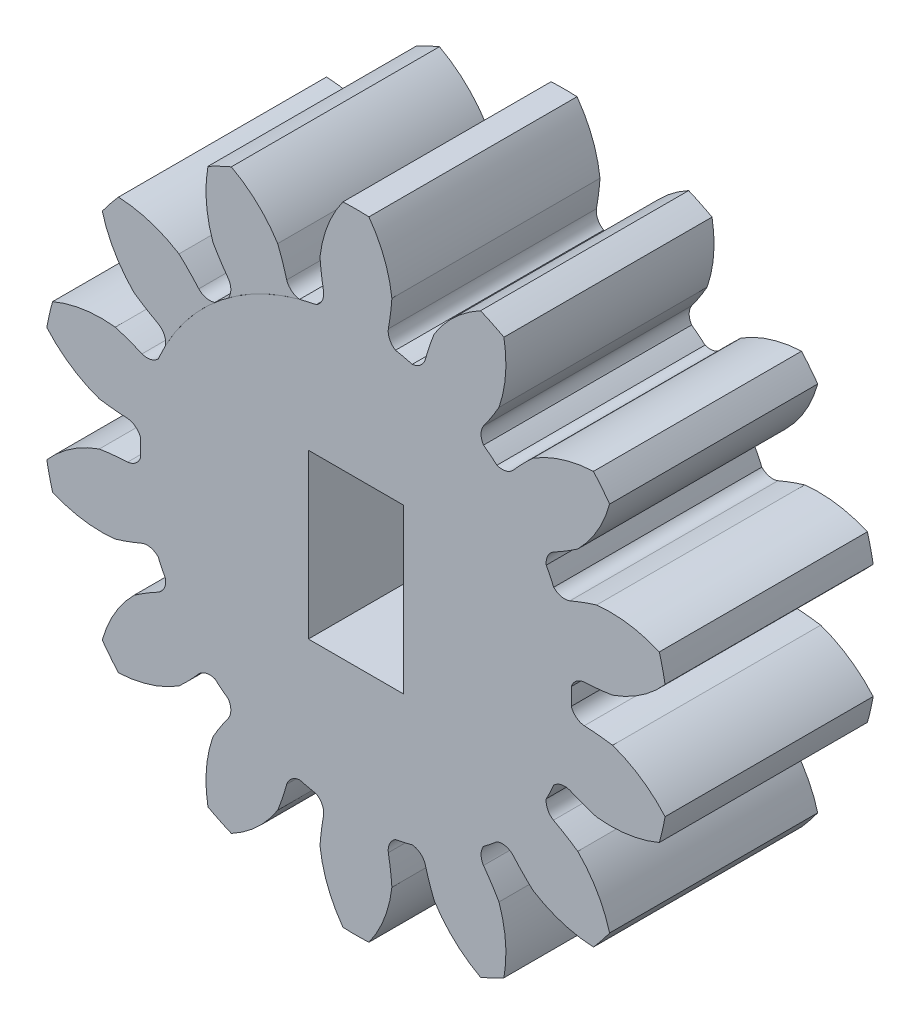
SolidWorks part; units mm, degrees
ref_plane "Front Plane" through (0, 0, 0) normal (0, 0, 1) x (1, 0, 0)
ref_plane "Top Plane" through (0, 0, 0) normal (0, 1, 0) x (1, 0, 0)
ref_plane "Right Plane" through (0, 0, 0) normal (1, 0, 0) x (0, 0, -1)
ref_plane "Plane1" through (0, 0, 20) normal (0, 0, 1) x (1, 0, 0)
ref_plane "Plane2" through (0, 0, 27) normal (0, 0, 1) x (1, 0, 0)
sketch "Sketch1" plane through (0, 0, 20) normal (0, 0, 1) x (1, 0, 0)
  circle A1 centre (0, 20.9252) radius 7.25
  dimension "D1" = 14.5
sketch "Sketch2" plane through (0, 0, 20) normal (0, 0, 1) x (1, 0, 0)
  arc A0 (-0.4364, 31.4909) -> (0.4364, 31.4909) centre (0, 22.3663) cw
  arc A1 (0.4364, 31.4909) -> (1.2091, 29.5028) centre (-2.9453, 29.0324) cw
  arc A2 (1.2091, 29.5028) -> (1.0888, 28.5542) centre (-7.3823, 30.1104) cw
  arc A3 (1.0888, 28.5542) -> (1.3305, 28.0521) centre (1.5953, 28.4888) ccw
  circle A4 centre (0, 20.9252) radius 7.25 construction
  arc A5 (-1.0888, 28.5542) -> (-1.3305, 28.0521) centre (-1.5953, 28.4888) cw
  arc A6 (-1.2091, 29.5028) -> (-1.0888, 28.5542) centre (7.3823, 30.1104) ccw
  arc A7 (-0.4364, 31.4909) -> (-1.2091, 29.5028) centre (2.9453, 29.0324) ccw
  arc A8 (-1.3305, 28.0521) -> (1.3305, 28.0521) centre (0, 20.9252) cw
  arc A9 (1.8935, 27.9236) -> (4.291, 26.769) centre (0, 20.9252) cw
  arc A10 (4.291, 27.3263) -> (4.291, 26.769) centre (4.719, 27.0476) ccw
  arc A11 (4.811, 28.1288) -> (4.291, 27.3263) centre (-2.6659, 32.4038) cw
  arc A12 (4.9774, 30.2553) -> (4.811, 28.1288) centre (0.8639, 29.5075) cw
  arc A13 (4.1911, 30.6339) -> (4.9774, 30.2553) centre (0.6252, 22.2236) cw
  arc A14 (4.1911, 30.6339) -> (2.6323, 29.178) centre (6.1712, 26.9516) ccw
  arc A15 (2.6323, 29.178) -> (2.3291, 28.2711) centre (10.6365, 25.9977) ccw
  arc A16 (2.3291, 28.2711) -> (1.8935, 27.9236) centre (1.8444, 28.432) cw
  arc A17 (4.7424, 26.409) -> (6.4016, 24.3285) centre (0, 20.9252) cw
  arc A18 (6.6434, 24.8306) -> (6.4016, 24.3285) centre (6.9081, 24.3938) ccw
  arc A19 (7.4601, 25.328) -> (6.6434, 24.8306) centre (2.5785, 32.4238) cw
  arc A20 (8.5327, 27.1717) -> (7.4601, 25.328) centre (4.502, 28.2827) cw
  arc A21 (7.9885, 27.854) -> (8.5327, 27.1717) centre (1.1267, 21.8237) cw
  arc A22 (7.9885, 27.854) -> (5.9524, 27.2186) centre (8.1748, 23.6772) ccw
  arc A23 (5.9524, 27.2186) -> (5.2857, 26.533) centre (11.784, 20.8804) ccw
  arc A24 (5.2857, 26.533) -> (4.7424, 26.409) centre (4.9188, 26.8883) cw
  arc A25 (6.6521, 23.8083) -> (7.2442, 21.2139) centre (0, 20.9252) cw
  arc A26 (7.68, 21.5614) -> (7.2442, 21.2139) centre (7.729, 21.053) ccw
  arc A27 (8.6316, 21.6552) -> (7.68, 21.5614) centre (7.3121, 30.1663) cw
  arc A28 (10.3979, 22.8509) -> (8.6316, 21.6552) centre (7.2485, 25.6007) cw
  arc A29 (10.2037, 23.7018) -> (10.3979, 22.8509) centre (1.4049, 21.2459) cw
  arc A30 (10.2037, 23.7018) -> (8.0935, 24.0127) centre (8.5593, 19.8578) ccw
  arc A31 (8.0935, 24.0127) -> (7.1954, 23.6843) centre (10.5976, 15.7719) ccw
  arc A32 (7.1954, 23.6843) -> (6.6521, 23.8083) centre (7.019, 24.1636) cw
  arc A33 (7.2442, 20.6365) -> (6.6521, 18.0422) centre (0, 20.9252) cw
  arc A34 (7.1954, 18.1662) -> (6.6521, 18.0422) centre (7.019, 17.6869) ccw
  arc A35 (8.0935, 17.8378) -> (7.1954, 18.1662) centre (10.5976, 26.0785) cw
  arc A36 (10.2037, 18.1487) -> (8.0935, 17.8378) centre (8.5593, 21.9927) cw
  arc A37 (10.3979, 18.9996) -> (10.2037, 18.1487) centre (1.4049, 20.6046) cw
  arc A38 (10.3979, 18.9996) -> (8.6316, 20.1953) centre (7.2485, 16.2497) ccw
  arc A39 (8.6316, 20.1953) -> (7.68, 20.2891) centre (7.3121, 11.6842) ccw
  arc A40 (7.68, 20.2891) -> (7.2442, 20.6365) centre (7.729, 20.7975) cw
  arc A41 (6.4016, 17.522) -> (4.7424, 15.4415) centre (0, 20.9252) cw
  arc A42 (5.2857, 15.3174) -> (4.7424, 15.4415) centre (4.9188, 14.9621) ccw
  arc A43 (5.9524, 14.6319) -> (5.2857, 15.3174) centre (11.784, 20.9701) cw
  arc A44 (7.9885, 13.9965) -> (5.9524, 14.6319) centre (8.1748, 18.1733) cw
  arc A45 (8.5327, 14.6788) -> (7.9885, 13.9965) centre (1.1267, 20.0268) cw
  arc A46 (8.5327, 14.6788) -> (7.4601, 16.5225) centre (4.502, 13.5677) ccw
  arc A47 (7.4601, 16.5225) -> (6.6434, 17.0199) centre (2.5785, 9.4267) ccw
  arc A48 (6.6434, 17.0199) -> (6.4016, 17.522) centre (6.9081, 17.4567) cw
  arc A49 (4.291, 15.0815) -> (1.8935, 13.9269) centre (0, 20.9252) cw
  arc A50 (2.3291, 13.5794) -> (1.8935, 13.9269) centre (1.8444, 13.4185) ccw
  arc A51 (2.6323, 12.6725) -> (2.3291, 13.5794) centre (10.6365, 15.8528) cw
  arc A52 (4.1911, 11.2165) -> (2.6323, 12.6725) centre (6.1712, 14.8989) cw
  arc A53 (4.9774, 11.5952) -> (4.1911, 11.2165) centre (0.6252, 19.6269) cw
  arc A54 (4.9774, 11.5952) -> (4.811, 13.7217) centre (0.8639, 12.343) ccw
  arc A55 (4.811, 13.7217) -> (4.291, 14.5242) centre (-2.6659, 9.4467) ccw
  arc A56 (4.291, 14.5242) -> (4.291, 15.0815) centre (4.719, 14.8028) cw
  arc A57 (1.3305, 13.7984) -> (-1.3305, 13.7984) centre (0, 20.9252) cw
  arc A58 (-1.0888, 13.2963) -> (-1.3305, 13.7984) centre (-1.5953, 13.3616) ccw
  arc A59 (-1.2091, 12.3476) -> (-1.0888, 13.2963) centre (7.3823, 11.7401) cw
  arc A60 (-0.4364, 10.3595) -> (-1.2091, 12.3476) centre (2.9453, 12.8181) cw
  arc A61 (0.4364, 10.3595) -> (-0.4364, 10.3595) centre (0, 19.4842) cw
  arc A62 (0.4364, 10.3595) -> (1.2091, 12.3476) centre (-2.9453, 12.8181) ccw
  arc A63 (1.2091, 12.3476) -> (1.0888, 13.2963) centre (-7.3823, 11.7401) ccw
  arc A64 (1.0888, 13.2963) -> (1.3305, 13.7984) centre (1.5953, 13.3616) cw
  arc A65 (-1.8935, 13.9269) -> (-4.291, 15.0815) centre (0, 20.9252) cw
  arc A66 (-4.291, 14.5242) -> (-4.291, 15.0815) centre (-4.719, 14.8028) ccw
  arc A67 (-4.811, 13.7217) -> (-4.291, 14.5242) centre (2.6659, 9.4467) cw
  arc A68 (-4.9774, 11.5952) -> (-4.811, 13.7217) centre (-0.8639, 12.343) cw
  arc A69 (-4.1911, 11.2165) -> (-4.9774, 11.5952) centre (-0.6252, 19.6269) cw
  arc A70 (-4.1911, 11.2165) -> (-2.6323, 12.6725) centre (-6.1712, 14.8989) ccw
  arc A71 (-2.6323, 12.6725) -> (-2.3291, 13.5794) centre (-10.6365, 15.8528) ccw
  arc A72 (-2.3291, 13.5794) -> (-1.8935, 13.9269) centre (-1.8444, 13.4185) cw
  arc A73 (-4.7424, 15.4415) -> (-6.4016, 17.522) centre (0, 20.9252) cw
  arc A74 (-6.6434, 17.0199) -> (-6.4016, 17.522) centre (-6.9081, 17.4567) ccw
  arc A75 (-7.4601, 16.5225) -> (-6.6434, 17.0199) centre (-2.5785, 9.4267) cw
  arc A76 (-8.5327, 14.6788) -> (-7.4601, 16.5225) centre (-4.502, 13.5677) cw
  arc A77 (-7.9885, 13.9965) -> (-8.5327, 14.6788) centre (-1.1267, 20.0268) cw
  arc A78 (-7.9885, 13.9965) -> (-5.9524, 14.6319) centre (-8.1748, 18.1733) ccw
  arc A79 (-5.9524, 14.6319) -> (-5.2857, 15.3174) centre (-11.784, 20.9701) ccw
  arc A80 (-5.2857, 15.3174) -> (-4.7424, 15.4415) centre (-4.9188, 14.9621) cw
  arc A81 (-6.6521, 18.0422) -> (-7.2442, 20.6365) centre (0, 20.9252) cw
  arc A82 (-7.68, 20.2891) -> (-7.2442, 20.6365) centre (-7.729, 20.7975) ccw
  arc A83 (-8.6316, 20.1953) -> (-7.68, 20.2891) centre (-7.3121, 11.6842) cw
  arc A84 (-10.3979, 18.9996) -> (-8.6316, 20.1953) centre (-7.2485, 16.2497) cw
  arc A85 (-10.2037, 18.1487) -> (-10.3979, 18.9996) centre (-1.4049, 20.6046) cw
  arc A86 (-10.2037, 18.1487) -> (-8.0935, 17.8378) centre (-8.5593, 21.9927) ccw
  arc A87 (-8.0935, 17.8378) -> (-7.1954, 18.1662) centre (-10.5976, 26.0785) ccw
  arc A88 (-7.1954, 18.1662) -> (-6.6521, 18.0422) centre (-7.019, 17.6869) cw
  arc A89 (-7.2442, 21.2139) -> (-6.6521, 23.8083) centre (0, 20.9252) cw
  arc A90 (-7.1954, 23.6843) -> (-6.6521, 23.8083) centre (-7.019, 24.1636) ccw
  arc A91 (-8.0935, 24.0127) -> (-7.1954, 23.6843) centre (-10.5976, 15.7719) cw
  arc A92 (-10.2037, 23.7018) -> (-8.0935, 24.0127) centre (-8.5593, 19.8578) cw
  arc A93 (-10.3979, 22.8509) -> (-10.2037, 23.7018) centre (-1.4049, 21.2459) cw
  arc A94 (-10.3979, 22.8509) -> (-8.6316, 21.6552) centre (-7.2485, 25.6007) ccw
  arc A95 (-8.6316, 21.6552) -> (-7.68, 21.5614) centre (-7.3121, 30.1663) ccw
  arc A96 (-7.68, 21.5614) -> (-7.2442, 21.2139) centre (-7.729, 21.053) cw
  arc A97 (-6.4016, 24.3285) -> (-4.7424, 26.409) centre (0, 20.9252) cw
  arc A98 (-5.2857, 26.533) -> (-4.7424, 26.409) centre (-4.9188, 26.8883) ccw
  arc A99 (-5.9524, 27.2186) -> (-5.2857, 26.533) centre (-11.784, 20.8804) cw
  arc A100 (-7.9885, 27.854) -> (-5.9524, 27.2186) centre (-8.1748, 23.6772) cw
  arc A101 (-8.5327, 27.1717) -> (-7.9885, 27.854) centre (-1.1267, 21.8237) cw
  arc A102 (-8.5327, 27.1717) -> (-7.4601, 25.328) centre (-4.502, 28.2827) ccw
  arc A103 (-7.4601, 25.328) -> (-6.6434, 24.8306) centre (-2.5785, 32.4238) ccw
  arc A104 (-6.6434, 24.8306) -> (-6.4016, 24.3285) centre (-6.9081, 24.3938) cw
  arc A105 (-4.291, 26.769) -> (-1.8935, 27.9236) centre (0, 20.9252) cw
  arc A106 (-2.3291, 28.2711) -> (-1.8935, 27.9236) centre (-1.8444, 28.432) ccw
  arc A107 (-2.6323, 29.178) -> (-2.3291, 28.2711) centre (-10.6365, 25.9977) cw
  arc A108 (-4.1911, 30.6339) -> (-2.6323, 29.178) centre (-6.1712, 26.9516) cw
  arc A109 (-4.9774, 30.2553) -> (-4.1911, 30.6339) centre (-0.6252, 22.2236) cw
  arc A110 (-4.9774, 30.2553) -> (-4.811, 28.1288) centre (-0.8639, 29.5075) ccw
  arc A111 (-4.811, 28.1288) -> (-4.291, 27.3263) centre (2.6659, 32.4038) ccw
  arc A112 (-4.291, 27.3263) -> (-4.291, 26.769) centre (-4.719, 27.0476) cw
  point P192 (0, 20.9252)
  dimension "D1" = 14
extrude "Boss-Extrude1" add sketch "Sketch2" along normal blind 7
extrude "Boss-Extrude2" add sketch "Sketch1" along normal blind 7
sketch "Sketch3" plane through (0, 0, 27) normal (0, 0, 1) x (1, 0, 0)
  line L0 (-3.9726, 20.9252) -> (15.3734, 20.9252) construction
  line L1 (0, 24.8978) -> (0, 8.7425) construction
  line L3 (-1.6, 23.6752) -> (1.6, 23.6752)
  line L4 (-1.6, 23.6752) -> (-1.6, 18.1752)
  line L5 (-1.6, 18.1752) -> (1.6, 18.1752)
  line L6 (1.6, 23.6752) -> (1.6, 18.1752)
  point P12 (0, 0)
  dimension "D1" = 3.2
  dimension "D2" = 5.5
  dimension "D3" = 1.6
  dimension "D4" = 2.75
extrude "Cut-Extrude1" cut sketch "Sketch3" against normal blind 6
